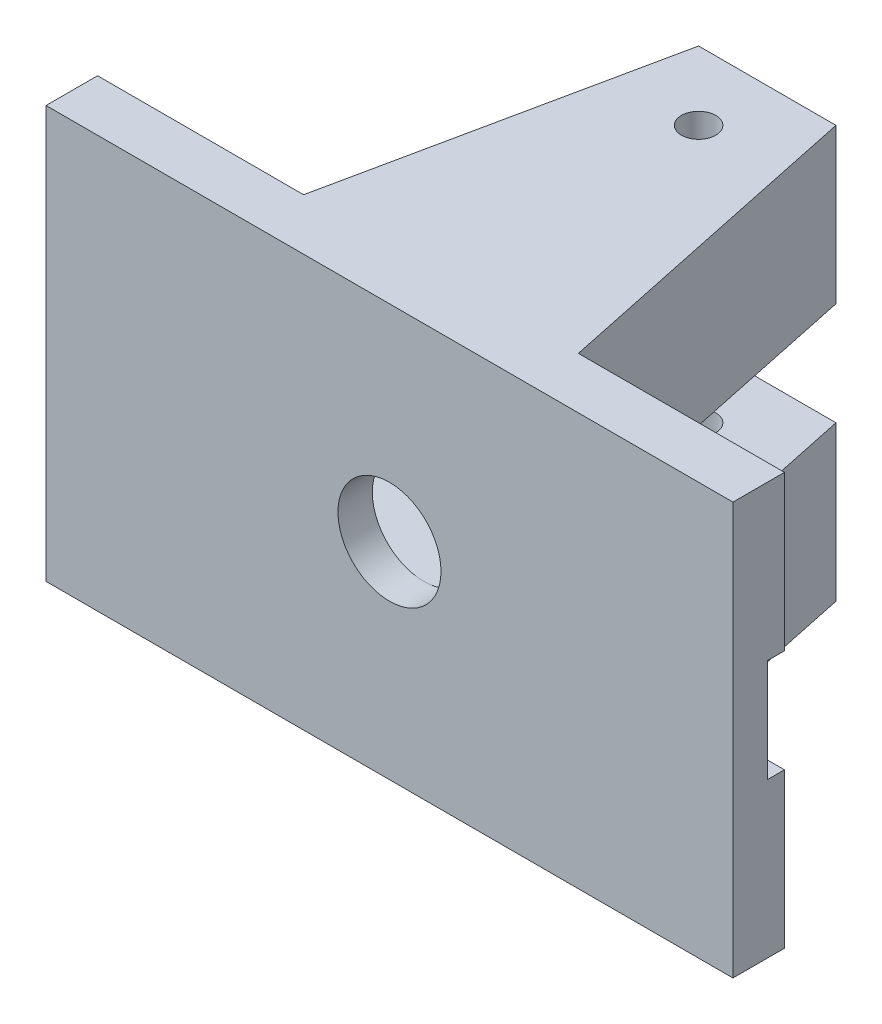
SolidWorks part; units mm, degrees
ref_plane "前视基准面" through (0, 0, 0) normal (0, 0, 1) x (1, 0, 0)
ref_plane "上视基准面" through (0, 0, 0) normal (0, 1, 0) x (1, 0, 0)
ref_plane "右视基准面" through (0, 0, 0) normal (1, 0, 0) x (0, 0, -1)
sketch "草图1" plane through (0, 0, 0) normal (0, 0, 1) x (1, 0, 0)
  line L1 (100, -60) -> (-100, -60)
  line L2 (100, -60) -> (100, 60)
  line L3 (100, 60) -> (-100, 60)
  line L4 (-100, -60) -> (-100, 60)
  line L5 (100, -60) -> (-100, 60) construction
  line L6 (100, 60) -> (-100, -60) construction
  circle A0 centre (0, 0) radius 15
  point P0 (0, 0)
  dimension "D1" = 120
  dimension "D2" = 200
extrude "凸台-拉伸1" add sketch "草图1" along normal blind 10
sketch "草图2" plane through (0, 0, 0) normal (0, 0, -1) x (-1, 0, 0)
  line L0 (100, 60) -> (100, -60) construction
  line L1 (-100, 60) -> (100, 60)
  line L2 (-100, 60) -> (-100, 15)
  line L3 (-100, 15) -> (100, 15)
  line L4 (100, 60) -> (100, 15)
  line L5 (15, 0) -> (62.3897, 0) construction
  line L6 (100, -60) -> (100, -15)
  line L7 (-100, -60) -> (100, -60)
  line L8 (-100, -15) -> (100, -15)
  line L9 (-100, -60) -> (-100, -15)
  circle A0 centre (0, 0) radius 15 construction
  dimension "D1" = 45
extrude "凸台-拉伸2" add sketch "草图2" along normal blind 100
sketch "草图3" plane through (0, 60, 0) normal (0, 1, 0) x (1, 0, 0)
  line L0 (-100, 5) -> (-100, 100)
  line L1 (-100, -10) -> (-100, 100) construction
  line L2 (-100, 5) -> (-40, 5)
  line L3 (-100, 100) -> (100, 100) construction
  line L4 (0, 100) -> (0, 39.8308) construction
  line L5 (100, 100) -> (20, 100)
  line L6 (-40, 5) -> (-20, 100)
  line L7 (-100, 100) -> (-20, 100)
  line L8 (100, 5) -> (100, 100)
  line L9 (100, 5) -> (40, 5)
  line L10 (40, 5) -> (20, 100)
  circle A0 centre (0, 80) radius 5
  dimension "D3" = 10
  dimension "D1" = 95
  dimension "D2" = 80
  dimension "D4" = 20
  dimension "D5" = 60
extrude "切除-拉伸1" cut sketch "草图3" against normal through all
